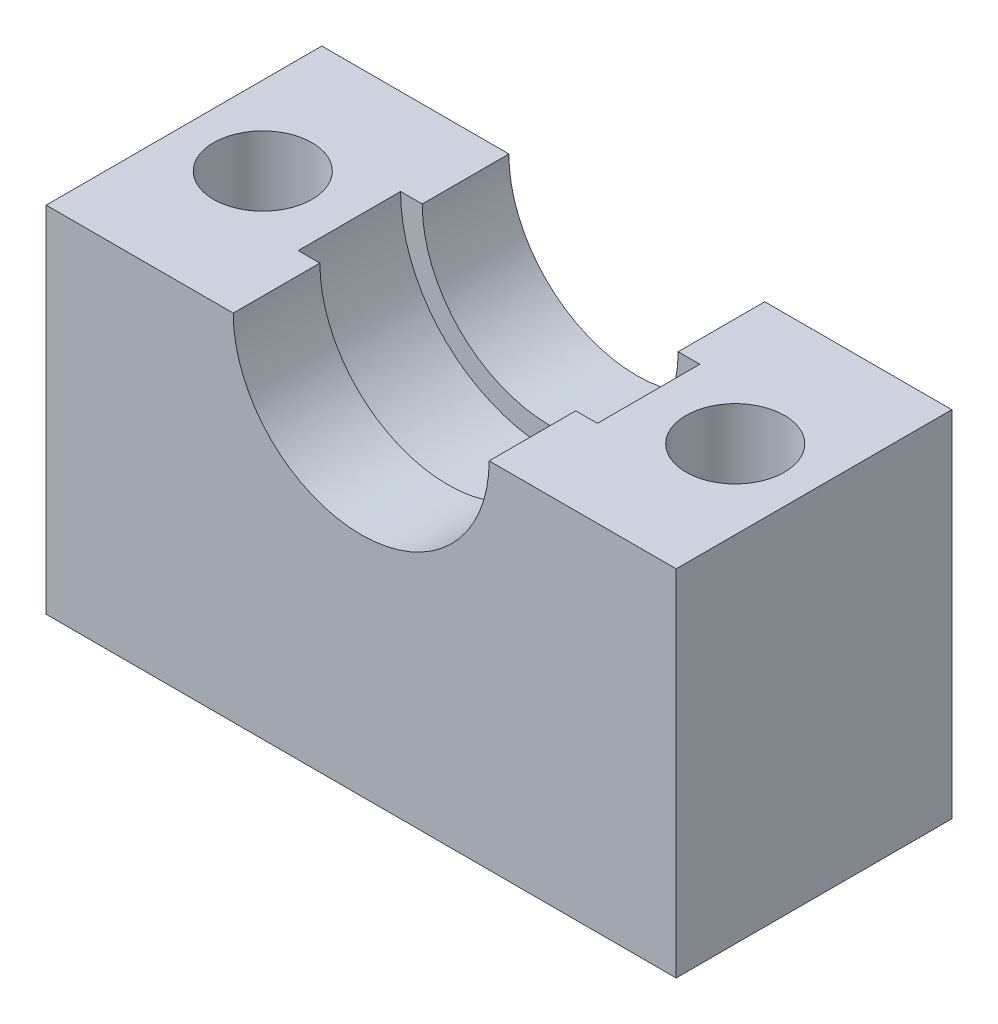
SolidWorks part; units mm, degrees
ref_plane "前基準面" through (0, 0, 0) normal (0, 0, 1) x (1, 0, 0)
ref_plane "上基準面" through (0, 0, 0) normal (0, 1, 0) x (1, 0, 0)
ref_plane "右基準面" through (0, 0, 0) normal (1, 0, 0) x (0, 0, -1)
sketch "草圖1" plane through (0, 0, 0) normal (0, 1, 0) x (1, 0, 0)
  line L1 (-16, -7) -> (16, -7)
  line L2 (-16, -7) -> (-16, 7)
  line L3 (-16, 7) -> (16, 7)
  line L4 (16, -7) -> (16, 7)
  line L5 (-16, -7) -> (16, 7) construction
  line L6 (-16, 7) -> (16, -7) construction
  point P0 (0, 0)
  dimension "D1" = 14
  dimension "D2" = 32
extrude "填料-伸長1" add sketch "草圖1" along normal blind 18
sketch "草圖3" plane through (0, 0, 0) normal (0, 0, 1) x (1, 0, 0)
  line L0 (16, 18) -> (-16, 18) construction
  line L1 (0, 0) -> (0, 18) construction
  circle A0 centre (0, 18) radius 7.6
  dimension "D1" = 15.2
extrude "除料-伸長1" cut sketch "草圖3" against normal mid plane 5.2
sketch "草圖4" plane through (0, 0, 0) normal (0, 0, 1) x (1, 0, 0)
  circle A0 centre (0, 18) radius 6.5
  dimension "D1" = 13
extrude "除料-伸長2" cut sketch "草圖4" against normal through all both and the other way through all
ref_plane "Plane1" through (0, 9, 0) normal (0, 1, 0) x (1, 0, 0)
sketch "草圖5" plane through (0, 18, 0) normal (0, 1, 0) x (1, 0, 0)
  line L0 (-12, 0) -> (0, 0) construction
  line L1 (0, 0) -> (0, 10.5657) construction
  circle A0 centre (-12, 0) radius 2.5
  circle A1 centre (12, 0) radius 2.5
  dimension "D1" = 5
  dimension "D2" = 24
extrude "除料-伸長3" cut sketch "草圖5" against normal blind 5.5
sketch "草圖6" plane through (0, 0, 7) normal (0, 0, 1) x (1, 0, 0)
  line L0 (-16, 9) -> (0, 9) construction
  line L1 (-16, 18) -> (-16, 0) construction
  line L2 (0, 9) -> (0, 0) construction
  line L3 (-16, 0) -> (16, 0) construction
  line L4 (-9.5, 18) -> (-14.5, 18) construction
  line L5 (-9.5, 18) -> (-14.5, 18) construction
  line L7 (-12, 18) -> (-12, 0) construction
  line L8 (-14.75, 2.8) -> (-9.25, 5.2) construction
  line L9 (-14.75, 12.8) -> (-9.25, 12.8)
  line L10 (-14.75, 12.8) -> (-14.75, 15.2)
  line L11 (-14.75, 15.2) -> (-9.25, 15.2)
  line L12 (-9.25, 12.8) -> (-9.25, 15.2)
  line L13 (-14.75, 12.8) -> (-9.25, 15.2) construction
  line L14 (-14.75, 15.2) -> (-9.25, 12.8) construction
  line L15 (-14.75, 5.2) -> (-9.25, 2.8) construction
  line L16 (-9.25, 5.2) -> (-9.25, 2.8)
  line L17 (-14.75, 2.8) -> (-9.25, 2.8)
  line L18 (-14.75, 5.2) -> (-14.75, 2.8)
  line L19 (-14.75, 5.2) -> (-9.25, 5.2)
  line L20 (14.75, 5.2) -> (9.25, 2.8) construction
  line L21 (14.75, 2.8) -> (9.25, 5.2) construction
  line L22 (14.75, 5.2) -> (9.25, 5.2)
  line L23 (14.75, 5.2) -> (14.75, 2.8)
  line L24 (14.75, 2.8) -> (9.25, 2.8)
  line L25 (9.25, 5.2) -> (9.25, 2.8)
  line L26 (14.75, 15.2) -> (9.25, 12.8) construction
  line L27 (14.75, 12.8) -> (9.25, 15.2) construction
  line L28 (9.25, 12.8) -> (9.25, 15.2)
  line L29 (14.75, 15.2) -> (9.25, 15.2)
  line L30 (14.75, 12.8) -> (14.75, 15.2)
  line L31 (14.75, 12.8) -> (9.25, 12.8)
  line L32 (-16, 18) -> (-6.5, 18) construction
  point P9 (-12, 14)
  point P20 (-12, 4)
  point P25 (12, 4)
  point P30 (12, 14)
  dimension "D1" = 2.4
  dimension "D2" = 5.5
  dimension "D3" = 4
extrude "除料-伸長4" [suppressed] cut sketch "草圖6" against normal through all
sketch "草圖7" plane through (0, 0, 7) normal (0, 0, 1) x (1, 0, 0)
  line L0 (-6.5, 18) -> (-9.5, 18)
  line L1 (6.5, 18) -> (9.5, 18)
  arc A0 (-6.5, 18) -> (6.5, 18) centre (0, 18) ccw construction
  arc A1 (-6.5, 18) -> (6.5, 18) centre (0, 18) ccw
  arc A2 (-9.5, 18) -> (9.5, 18) centre (0, 18) ccw
  dimension "D1" = 3
extrude "填料-伸長2" [suppressed] add sketch "草圖7" along normal blind 18
mirror "Mirror1" about plane through (0, 9, 0) normal (0, 1, 0) of "除料-伸長3"
